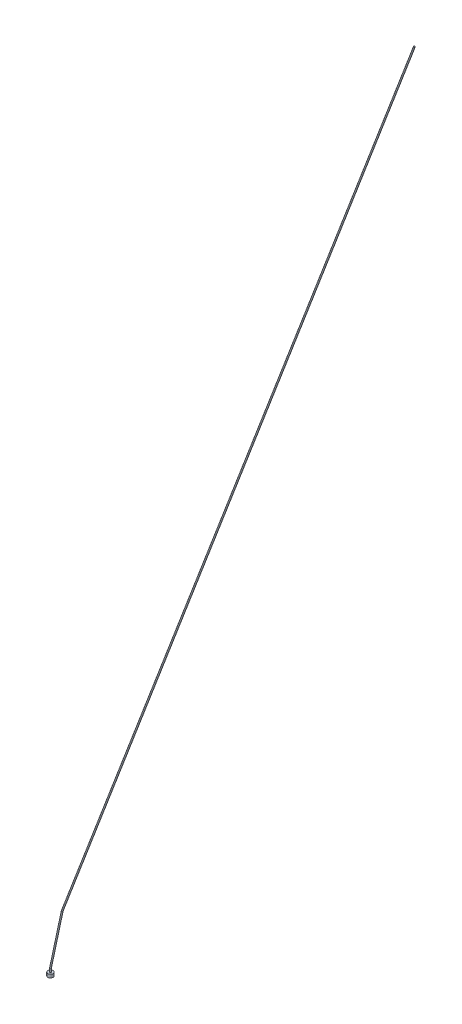
SolidWorks part; units mm, degrees
material "Nylon 6/10"
ref_plane "Front Plane" through (0, 0, 0) normal (0, 0, 1) x (1, 0, 0)
ref_plane "Top Plane" through (0, 0, 0) normal (0, 1, 0) x (1, 0, 0)
ref_plane "Right Plane" through (0, 0, 0) normal (1, 0, 0) x (0, 0, -1)
sketch "Sketch1" plane through (0, 0, 0) normal (0, 0, 1) x (1, 0, 0)
  line L0 (55, -42.5) -> (73, 42.5)
  line L1 (-73, 42.5) -> (73, 42.5) construction
  line L2 (-73, 42.5) -> (-73, -42.5) construction
  line L3 (-73, -42.5) -> (73, -42.5) construction
  line L4 (73, 42.5) -> (73, -42.5) construction
  line L5 (-73, 42.5) -> (73, -42.5) construction
  line L6 (-73, -42.5) -> (73, 42.5) construction
  line L7 (73, 42.5) -> (611.965, 1457.5)
  line L8 (55, -42.5) -> (55, -52.5)
  point P0 (0, 0)
  point P9 (55, -42.5)
  point P11 (611.965, 1457.5)
  dimension "D1" = 85
  dimension "D2" = 146
  dimension "D3" = 611.965
  dimension "D4" = 1500
  dimension "D5" = 55
  dimension "D6" = 10
sweep "Sweep1" add path "Sketch1" circular profile diameter 2 parameters "D3"=2
sketch "Sketch10" plane through (0, -52.5, 0) normal (0, -1, 0) x (1, 0, 0)
  circle A0 centre (55, 0) radius 4
  dimension "D1" = 8
extrude "Boss-Extrude1" add sketch "Sketch10" against normal blind 5
